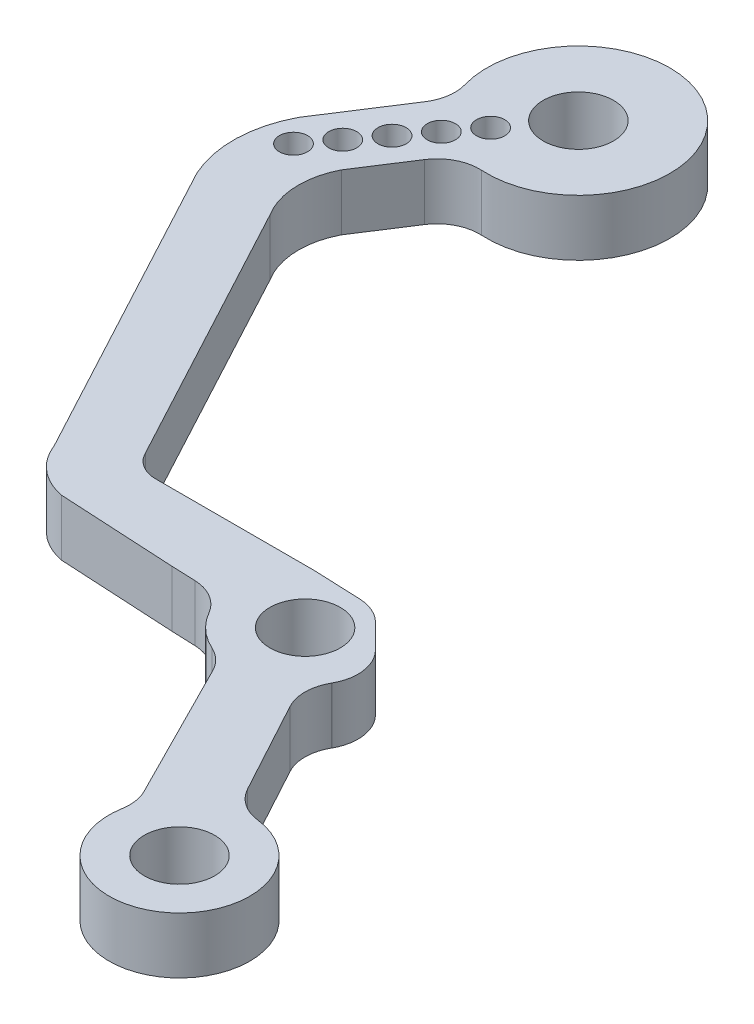
SolidWorks part; units mm, degrees
ref_plane "Front Plane" through (0, 0, 0) normal (0, 0, 1) x (1, 0, 0)
ref_plane "Top Plane" through (0, 0, 0) normal (0, 1, 0) x (1, 0, 0)
ref_plane "Right Plane" through (0, 0, 0) normal (1, 0, 0) x (0, 0, -1)
sketch "Sketch1" plane through (0, 0, 0) normal (0, 1, 0) x (1, 0, 0)
  line L0 (143.3333, 493) -> (716.6667, 493) construction
sketch "Sketch2" plane through (0, 0, 0) normal (0, 1, 0) x (1, 0, 0)
  line L0 (45.2788, 103.9326) -> (40.9177, 97.1844)
  line L1 (51.9956, 69.1217) -> (40.7298, 90.14)
  line L2 (58.0479, 69.8647) -> (65.4047, 69.8647)
  line L3 (64.0439, 65.0687) -> (56.5756, 65.4741)
  line L4 (49.0625, 100.7287) -> (45.662, 95.4669)
  line L5 (45.9135, 90.14) -> (56.2122, 70.926)
  line L6 (45.9135, 90.14) -> (45.5308, 90.8539)
  line L7 (65.4047, 69.8647) -> (69.3416, 69.8647)
  line L8 (77.3922, 49.2355) -> (71.3644, 61.1602)
  line L9 (69.3416, 69.8647) -> (73.8824, 69.6766)
  line L10 (73.8824, 69.6766) -> (77.5387, 66.0204)
  line L11 (51.9956, 69.1217) -> (52.4488, 68.2763)
  line L13 (56.9043, 65.4562) -> (55.7376, 65.5195)
  line L14 (81.2785, 52.4716) -> (75.9262, 62.3428)
  line L17 (64.0439, 65.0687) -> (67.6597, 64.927)
  circle A5 centre (72.5387, 66.0204) radius 2.5
  circle A7 centre (82.0956, 47.5388) radius 2.5
  arc A9 (45.662, 95.4669) -> (45.9135, 90.14) centre (50.4346, 93.0228) ccw
  arc A10 (41.6771, 98.3595) -> (40.7298, 90.14) centre (47.9508, 93.4721) ccw
  circle A11 centre (51.0536, 106.9163) radius 3.4
  arc A13 (52.4488, 68.2763) -> (55.7376, 65.5195) centre (56.5568, 69.837) ccw
  arc A14 (56.116, 71.1054) -> (58.0479, 69.8647) centre (58.0835, 72.0445) ccw
  arc A15 (67.6597, 64.927) -> (71.3644, 61.1602) centre (72.5387, 66.0204) ccw
  arc A16 (49.0625, 100.7287) -> (45.2788, 103.9326) centre (51.0536, 106.9163) ccw
  arc A17 (75.9262, 62.3428) -> (77.5387, 66.0204) centre (72.5387, 66.0204) ccw
  arc A19 (77.3922, 49.2355) -> (81.2785, 52.4716) centre (82.0956, 47.5388) ccw
extrude "Boss-Extrude1" add sketch "Sketch2" along normal blind 4
fillet "Fillet1" radius 3 9 edges at (77.5387, 2, -66.0204) (73.8824, 2, -69.6766) (75.9262, 2, -62.3428) (77.3922, 2, -49.2355) (81.2785, 2, -52.4716) (71.3644, 2, -61.1602) (67.6597, 2, -64.927) (45.2788, 2, -103.9326) (49.0625, 2, -100.7287)
sketch "Sketch3" plane through (0, 4, 0) normal (0, 1, 0) x (1, 0, 0)
  line L12 (76.8838, 63.5466) -> (76.8918, 63.5606)
  line L13 (76.4012, 67.1578) -> (74.7101, 68.8489)
  line L14 (72.7129, 69.725) -> (69.3416, 69.8647)
  line L15 (69.3416, 69.8647) -> (58.0479, 69.8647)
  line L16 (56.116, 71.1054) -> (45.9135, 90.14)
  line L17 (45.662, 95.4669) -> (47.9844, 99.0605)
  line L18 (44.4478, 102.6467) -> (40.9177, 97.1844)
  line L19 (40.7298, 90.14) -> (52.4488, 68.2763)
  line L20 (55.7376, 65.5195) -> (64.0439, 65.0687)
  line L21 (64.0439, 65.0687) -> (65.737, 65.0024)
  line L22 (71.9047, 60.0912) -> (76.8866, 50.2358)
  line L23 (80.4223, 54.0505) -> (76.8536, 60.6323)
  line L24 (76.8838, 63.5466) -> (76.8918, 63.5606)
  line L25 (76.4012, 67.1578) -> (74.7101, 68.8489)
  line L26 (72.7129, 69.725) -> (69.3416, 69.8647)
  line L27 (69.3416, 69.8647) -> (58.0479, 69.8647)
  line L28 (56.116, 71.1054) -> (45.9135, 90.14)
  line L29 (45.662, 95.4669) -> (47.9844, 99.0605)
  line L30 (44.4478, 102.6467) -> (40.9177, 97.1844)
  line L31 (40.7298, 90.14) -> (52.4488, 68.2763)
  line L32 (55.7376, 65.5195) -> (64.0439, 65.0687)
  line L33 (64.0439, 65.0687) -> (65.737, 65.0024)
  line L34 (71.9047, 60.0912) -> (76.8866, 50.2358)
  line L35 (80.4223, 54.0505) -> (76.8536, 60.6323)
  circle A0 centre (48.3743, 103.3632) radius 1 construction
  circle A1 centre (46.8691, 101.3672) radius 1 construction
  circle A2 centre (45.3638, 99.3711) radius 1 construction
  circle A3 centre (43.8586, 97.375) radius 1 construction
  circle A4 centre (42.3534, 95.379) radius 1 construction
  circle A5 centre (48.3743, 103.3632) radius 1
  circle A6 centre (46.8691, 101.3672) radius 1
  circle A7 centre (45.3638, 99.3711) radius 1
  circle A8 centre (43.8586, 97.375) radius 1
  circle A9 centre (42.3534, 95.379) radius 1
  arc A16 (76.8918, 63.5606) -> (76.4012, 67.1578) centre (74.2799, 65.0365) ccw
  arc A17 (74.7101, 68.8489) -> (72.7129, 69.725) centre (72.5888, 66.7276) ccw
  arc A18 (56.116, 71.1054) -> (58.0479, 69.8647) centre (58.0835, 72.0445) ccw
  arc A19 (45.662, 95.4669) -> (45.9135, 90.14) centre (50.4346, 93.0228) ccw
  arc A20 (50.6776, 100.4271) -> (47.9844, 99.0605) centre (50.504, 97.4322) ccw
  arc A21 (50.6776, 100.4271) -> (44.8098, 105.1091) centre (51.0536, 106.9163) ccw
  arc A22 (44.4478, 102.6467) -> (44.8098, 105.1091) centre (41.9281, 104.275) ccw
  arc A23 (40.9177, 97.1844) -> (40.7298, 90.14) centre (47.9508, 93.4721) ccw
  arc A24 (52.4488, 68.2763) -> (55.7376, 65.5195) centre (56.5568, 69.837) ccw
  arc A25 (68.2142, 63.5105) -> (65.737, 65.0024) centre (65.6195, 62.0047) ccw
  arc A26 (68.2142, 63.5105) -> (70.4691, 61.4688) centre (72.5387, 66.0204) ccw
  arc A27 (71.9047, 60.0912) -> (70.4691, 61.4688) centre (69.2274, 58.7378) ccw
  arc A28 (77.1666, 48.3786) -> (76.8866, 50.2358) centre (74.2092, 48.8824) ccw
  arc A29 (77.1666, 48.3786) -> (82.6981, 52.5023) centre (82.0956, 47.5388) ccw
  arc A30 (80.4223, 54.0505) -> (82.6981, 52.5023) centre (83.0596, 55.4805) ccw
  arc A31 (76.8838, 63.5466) -> (76.8536, 60.6323) centre (79.4909, 62.0623) ccw
  arc A32 (76.8918, 63.5606) -> (76.4012, 67.1578) centre (74.2799, 65.0365) ccw
  arc A33 (74.7101, 68.8489) -> (72.7129, 69.725) centre (72.5888, 66.7276) ccw
  arc A34 (56.116, 71.1054) -> (58.0479, 69.8647) centre (58.0835, 72.0445) ccw
  arc A35 (45.662, 95.4669) -> (45.9135, 90.14) centre (50.4346, 93.0228) ccw
  arc A36 (50.6776, 100.4271) -> (47.9844, 99.0605) centre (50.504, 97.4322) ccw
  arc A37 (50.6776, 100.4271) -> (44.8098, 105.1091) centre (51.0536, 106.9163) ccw
  arc A38 (44.4478, 102.6467) -> (44.8098, 105.1091) centre (41.9281, 104.275) ccw
  arc A39 (40.9177, 97.1844) -> (40.7298, 90.14) centre (47.9508, 93.4721) ccw
  arc A40 (52.4488, 68.2763) -> (55.7376, 65.5195) centre (56.5568, 69.837) ccw
  arc A41 (68.2142, 63.5105) -> (65.737, 65.0024) centre (65.6195, 62.0047) ccw
  arc A42 (68.2142, 63.5105) -> (70.4691, 61.4688) centre (72.5387, 66.0204) ccw
  arc A43 (71.9047, 60.0912) -> (70.4691, 61.4688) centre (69.2274, 58.7378) ccw
  arc A44 (77.1666, 48.3786) -> (76.8866, 50.2358) centre (74.2092, 48.8824) ccw
  arc A45 (77.1666, 48.3786) -> (82.6981, 52.5023) centre (82.0956, 47.5388) ccw
  arc A46 (80.4223, 54.0505) -> (82.6981, 52.5023) centre (83.0596, 55.4805) ccw
  arc A47 (76.8838, 63.5466) -> (76.8536, 60.6323) centre (79.4909, 62.0623) ccw
  dimension "D1" = 0
extrude "Cut-Extrude2" cut sketch "Sketch3" against normal up to surface (4 mm away) contours A9 | A8 | A7 | A6 | A5 up to face at (72.5387, 0, -63.5204)
ref_plane "Plane1" through (43.4413, 0, -103.0709) normal (-0.3884, 0, 0.9215) x (0.9215, 0, 0.3884)
sketch "Sketch4" plane through (0, 4, 0) normal (0, 1, 0) x (1, 0, 0)
  circle A0 centre (51.0536, 106.9163) radius 3.4 construction
  circle A1 centre (51.0536, 106.9163) radius 3.4
  point P3 (0, 0)
  point P4 (0, 0)
  point P5 (0, 0)
  point P6 (0, 0)
ref_plane "Plane3" through (45.9658, 0, -109.0606) normal (-0.3884, 0, 0.9215) x (0.9215, 0, 0.3884)
sketch "Sketch5" plane through (45.9658, 0, -109.0606) normal (-0.3884, 0, 0.9215) x (0.9215, 0, 0.3884)
  line L0 (8.9212, 4) -> (2.1212, 4) construction
  line L1 (3.0212, 4) -> (2.1212, 4)
  line L2 (2.1212, 4) -> (2.1212, 0)
  line L3 (2.1212, 0) -> (3.0212, 0)
  line L5 (3.0212, 4) -> (3.0212, 0)
  dimension "D1" = 0.9
sweep "Sweep1" add profiles "Sketch5" path "Sketch4"
